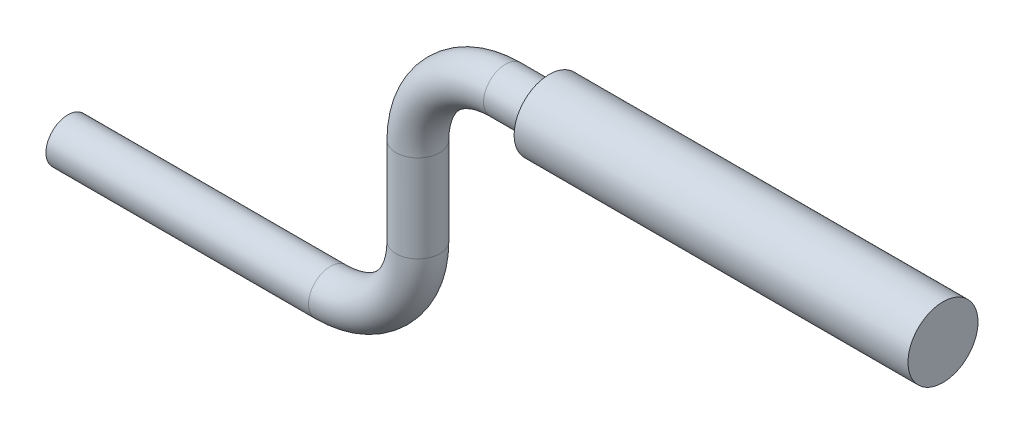
SolidWorks part; units mm, degrees
material "Alliage de zinc AC41A, brut"
ref_plane "Plan de face" through (0, 0, 0) normal (0, 0, 1) x (1, 0, 0)
ref_plane "Plan de dessus" through (0, 0, 0) normal (0, 1, 0) x (1, 0, 0)
ref_plane "Plan de droite" through (0, 0, 0) normal (1, 0, 0) x (0, 0, -1)
sketch "Esquisse1" plane through (0, 0, 0) normal (0, 0, 1) x (1, 0, 0)
  line L0 (0, 0) -> (30, 0)
  line L1 (40, 10) -> (40, 20)
  line L2 (50, 30) -> (100, 30)
  arc A0 (40, 20) -> (50, 30) centre (50, 20) cw
  arc A1 (30, 0) -> (40, 10) centre (30, 10) ccw
  point P7 (40, 30)
  point P10 (40, 0)
  dimension "D4" = 10
  dimension "D1" = 40
  dimension "D2" = 30
  dimension "D3" = 60
ref_plane "Plan1" through (100, 0, 0) normal (1, 0, 0) x (0, 0, -1)
sketch "Esquisse2" plane through (100, 0, 0) normal (1, 0, 0) x (0, 0, -1)
  circle A0 centre (0, 30) radius 2.5
  dimension "D1" = 5
sweep "Balayage1" add profiles "Esquisse2" path "Esquisse1"
sketch "Esquisse3" plane through (100, 0, 0) normal (1, 0, 0) x (0, 0, -1)
  circle A0 centre (0, 30) radius 4
  dimension "D1" = 8
extrude "Boss.-Extru.1" add sketch "Esquisse3" against normal blind 45
